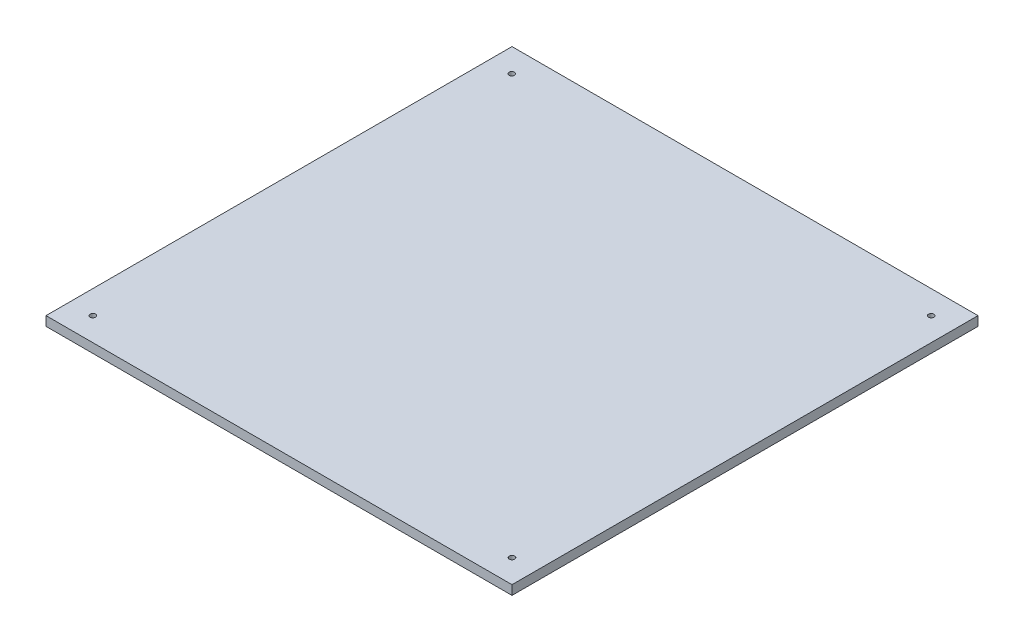
SolidWorks part; units mm, degrees
material "PETG"
ref_plane "Front Plane" through (0, 0, 0) normal (0, 0, 1) x (1, 0, 0)
ref_plane "Top Plane" through (0, 0, 0) normal (0, 1, 0) x (1, 0, 0)
ref_plane "Right Plane" through (0, 0, 0) normal (1, 0, 0) x (0, 0, -1)
sketch "Sketch3" plane through (0, 0, 0) normal (0, 1, 0) x (1, 0, 0)
  line L1 (-71.3744, 257.5054) -> (228.6256, 257.5054)
  line L2 (-71.3744, 257.5054) -> (-71.3744, -42.4946)
  line L3 (-71.3744, -42.4946) -> (228.6256, -42.4946)
  line L4 (228.6256, 257.5054) -> (228.6256, -42.4946)
  dimension "D1" = 300
extrude "Boss-Extrude1" add sketch "Sketch3" along normal blind 6
sketch "Sketch6" plane through (0, 6, 0) normal (0, 1, 0) x (1, 0, 0)
  circle A0 centre (-56.3041, 242.2488) radius 1.75
sketch "Sketch8" plane through (0, 6, 0) normal (0, 1, 0) x (1, 0, 0)
extrude "Cut-Extrude1" cut sketch "Sketch6" against normal blind 6 contours A0
sketch "Sketch15" plane through (0, 6, 0) normal (0, 1, 0) x (1, 0, 0)
  circle A0 centre (213.5175, -27.4069) radius 1.75
sketch "Sketch16" plane through (0, 6, 0) normal (0, 1, 0) x (1, 0, 0)
  circle A0 centre (-56.2884, -27.4279) radius 1.75
sketch "Sketch17" plane through (0, 6, 0) normal (0, 1, 0) x (1, 0, 0)
  circle A0 centre (213.5952, 242.4368) radius 1.75
extrude "Cut-Extrude6" cut sketch "Sketch15" against normal blind 6 contours A0
extrude "Cut-Extrude7" cut sketch "Sketch17" against normal blind 6 contours A0
extrude "Cut-Extrude8" cut sketch "Sketch16" against normal blind 6 contours A0
